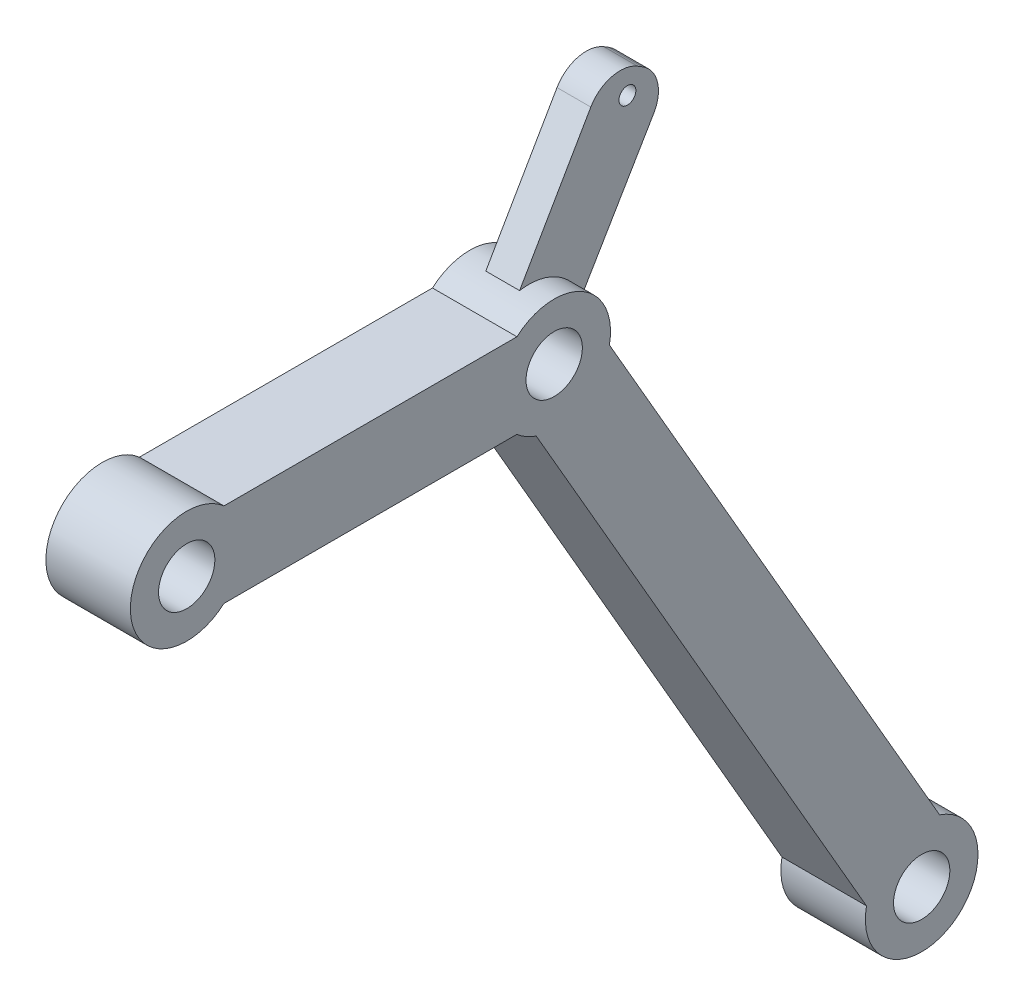
SolidWorks part; units mm, degrees
ref_plane "Front Plane" through (0, 0, 0) normal (0, 0, 1) x (1, 0, 0)
ref_plane "Top Plane" through (0, 0, 0) normal (0, 1, 0) x (1, 0, 0)
ref_plane "Right Plane" through (0, 0, 0) normal (1, 0, 0) x (0, 0, -1)
sketch "Sketch2" plane through (0, 0, 0) normal (1, 0, 0) x (0, 0, -1)
  line L0 (0, 0) -> (-130.5, 0)
  line L2 (0, -68.7308) -> (0, 133.8442) construction
  line L3 (0, 0) -> (130.5, -226.0326)
  dimension "D1" = 130.5
  dimension "D2" = 261
  dimension "D3" = 120
ref_plane "Plane2" through (0, 0, 130.5) normal (0, 0, 1) x (1, 0, 0)
sketch "Sketch7" plane through (0, 0, 130.5) normal (0, 0, 1) x (1, 0, 0)
  line L0 (12.5, 12.5) -> (12.5, -12.5)
  line L1 (-15, 15) -> (15, 15)
  line L2 (-15, 15) -> (-15, -15)
  line L3 (-15, -15) -> (15, -15)
  line L4 (15, 15) -> (15, -15)
  line L5 (-15, 15) -> (15, -15) construction
  line L6 (-15, -15) -> (15, 15) construction
  line L7 (-12.5, -12.5) -> (12.5, -12.5)
  line L8 (-12.5, 12.5) -> (-12.5, -12.5)
  line L9 (-12.5, 12.5) -> (12.5, 12.5)
  point P0 (0, 0)
  dimension "D1" = 30
  dimension "D2" = 30
  dimension "D3" = 2.5
sweep "Sweep4" add profiles "Sketch7" path "Sketch2"
sketch "Sketch8" plane through (15, 0, 0) normal (1, 0, 0) x (0, 0, -1)
  line L0 (-130.5, -15) -> (-130.5, 15) construction
  line L1 (117.5096, -233.5326) -> (143.4904, -218.5326) construction
  circle A0 centre (0, 0) radius 20
  circle A2 centre (-130.5, 0) radius 20
  circle A3 centre (130.5, -226.0326) radius 20
extrude "Boss-Extrude1" add sketch "Sketch8" against normal blind 30
sketch "Sketch9" plane through (15, 0, 0) normal (1, 0, 0) x (0, 0, -1)
  circle A0 centre (0, 0) radius 10
  circle A1 centre (-130.5, 0) radius 10
  circle A2 centre (130.5, -226.0326) radius 10
extrude "Cut-Extrude1" cut sketch "Sketch9" against normal blind 30
sketch "Sketch13" plane through (0, 0, 0) normal (1, 0, 0) x (0, 0, -1)
  line L0 (0, 0) -> (10, 17.3205) construction
  line L1 (10, 17.3205) -> (20, 34.641) construction
  line L4 (19.6048, -3.9564) -> (9.8596, 1.6699)
  line L5 (-3.4836, 9.3736) -> (-13.2288, 15)
  line L8 (20, 34.641) -> (35, 60.6218) construction
  line L9 (-3.2871, 19.728) -> (22.0003, 63.527)
  line L10 (38.6435, 67.7703) -> (40.2857, 66.7682)
  line L11 (44.3669, 50.4218) -> (18.7285, 7.0173)
  circle A0 centre (35, 60.6218) radius 3
  arc A1 (9.8596, 1.6699) -> (-3.4836, 9.3736) centre (0, 0) ccw
  arc A2 (-3.2871, 19.728) -> (-13.2288, 15) centre (0, 0) ccw
  arc A3 (19.6048, -3.9564) -> (18.7285, 7.0173) centre (0, 0) ccw
  arc A5 (19.6048, -3.9564) -> (-13.2288, 15) centre (0, 0) ccw construction
  arc A6 (40.2857, 66.7682) -> (44.3669, 50.4218) centre (34.0348, 56.5248) cw
  arc A7 (22.0003, 63.527) -> (38.6435, 67.7703) centre (32.3926, 57.527) cw
  dimension "D1" = 20
  dimension "D2" = 12.7107
  dimension "D3" = 8
  dimension "D4" = 12
  dimension "D5" = 30
  dimension "D6" = 180
extrude "Boss-Extrude2" add sketch "Sketch13" along normal mid plane 12
